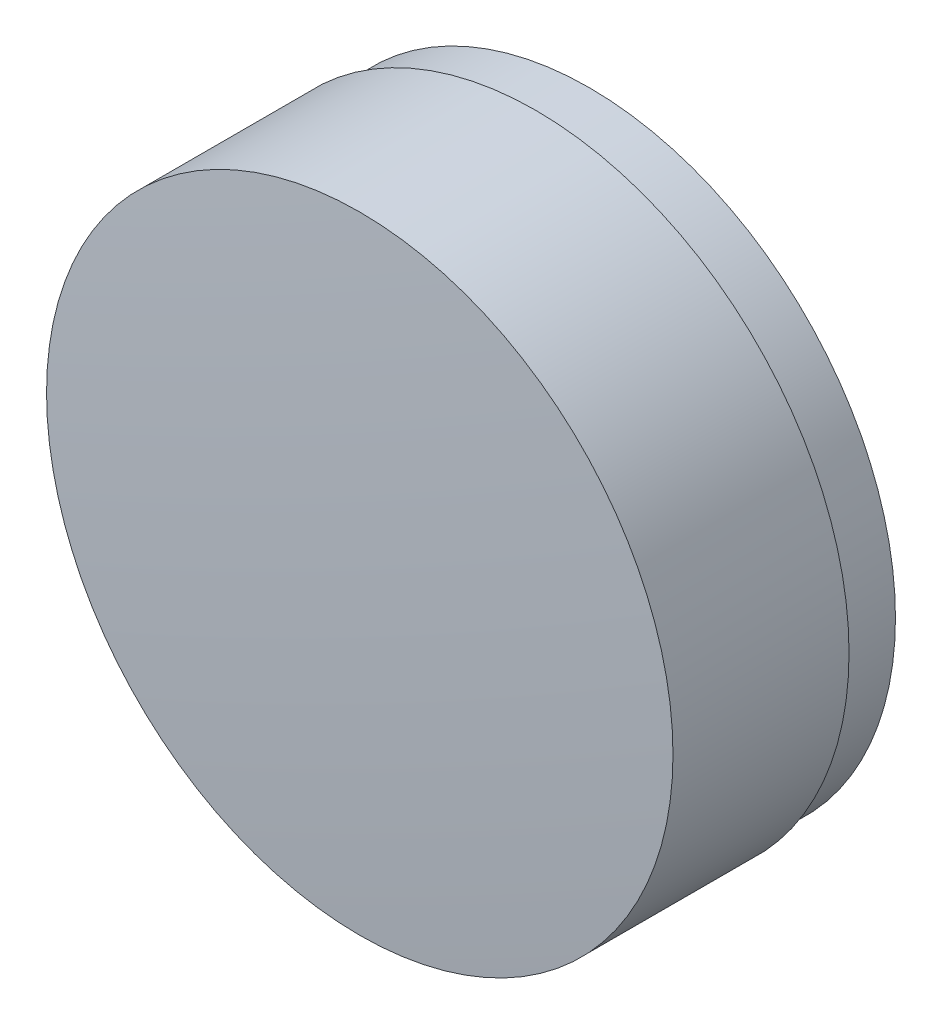
SolidWorks part; units mm, degrees
material "Polyester Resin"
ref_plane "Front Plane" through (0, 0, 0) normal (0, 0, 1) x (1, 0, 0)
ref_plane "Top Plane" through (0, 0, 0) normal (0, 1, 0) x (1, 0, 0)
ref_plane "Right Plane" through (0, 0, 0) normal (1, 0, 0) x (0, 0, -1)
sketch "Sketch1" plane through (0, 0, 0) normal (1, 0, 0) x (0, 0, -1)
  line L0 (0.6864, 5.35) -> (-0.25, 5.35)
  line L1 (-3.49, 0) -> (0, 0)
  line L2 (-3.3375, 5.3) -> (0.6734, 5.3) construction
  line L4 (2.1691, 0) -> (-5.856, 0) construction
  line L5 (-0.25, 5.475) -> (-3.3273, 5.475)
  line L7 (-0.25, 5.475) -> (-0.25, 8.8505) construction
  line L9 (-0.25, 5.35) -> (-0.25, 5.475)
  arc A0 (-3.3273, 5.475) -> (-3.49, 0) centre (88.7133, 0) ccw
  arc A1 (0.6864, 5.35) -> (0, 0) centre (21.193, 0) ccw
  arc A2 (0, 0) -> (0.6864, 5.35) centre (21.193, 0) cw construction
  dimension "D1" = 21.193
  dimension "D2" = 92.2033
  dimension "D3" = 10.7
  dimension "D4" = 3.49
  dimension "D5" = 10.6
  dimension "D9" = 10.95
  dimension "D16" = 0.25
  dimension "D17" = 0.125
revolve "Revolve1" add sketch "Sketch1" angle 360 about L4
sketch "Sketch2" plane through (0, 0, 0.25) normal (0, 0, -1) x (-1, 0, 0)
  line L0 (0, 0) -> (8.35, 0) construction
  line L1 (8.35, -1.25) -> (8.35, 1.25)
  line L2 (8.35, 1.25) -> (5.025, 1.8363)
  line L3 (5.025, 1.8363) -> (5.025, -1.8363)
  line L4 (8.35, -1.25) -> (5.025, -1.8363)
  circle A0 centre (0, 0) radius 5.35 construction
  circle A1 centre (0, 0) radius 5.35 construction
  point P12 (5.025, 0)
  dimension "D1" = 10
  dimension "D2" = 3
  dimension "D3" = 2.5
extrude "Gate" [suppressed] add sketch "Sketch2" against normal blind 2.5 draft 3
fillet "Fillet1" [suppressed] radius 0.7874
